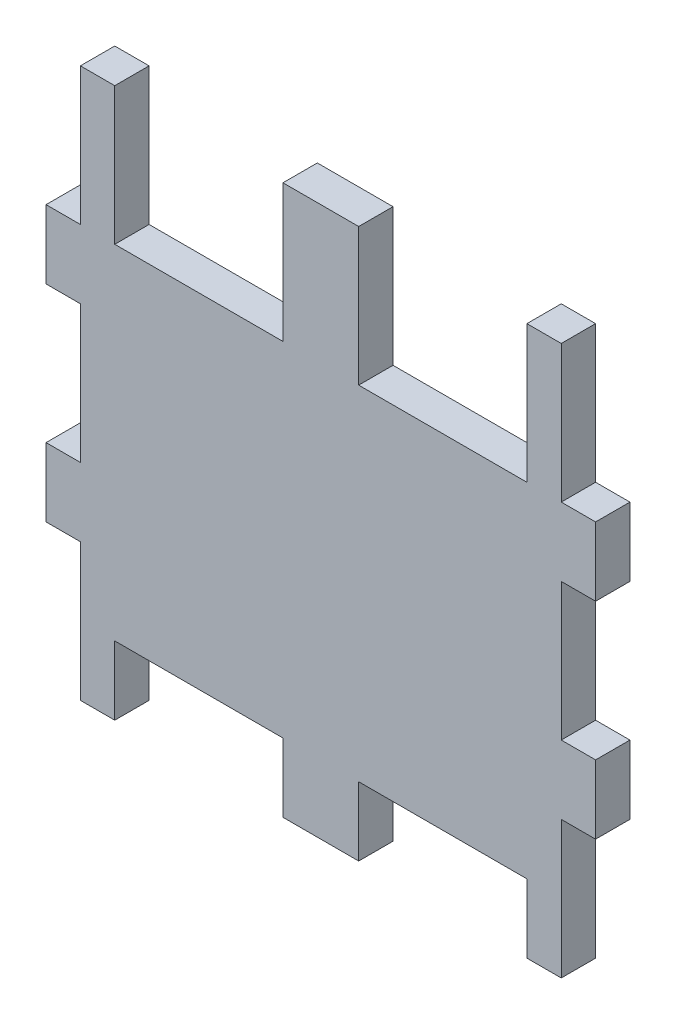
SolidWorks part; units mm, degrees
ref_plane "Front Plane" through (0, 0, 0) normal (0, 0, 1) x (1, 0, 0)
ref_plane "Top Plane" through (0, 0, 0) normal (0, 1, 0) x (1, 0, 0)
ref_plane "Right Plane" through (0, 0, 0) normal (1, 0, 0) x (0, 0, -1)
sketch "Sketch2" plane through (0, 0, 0) normal (0, 0, 1) x (1, 0, 0)
  line L1 (-50.8, -50.8) -> (50.8, -50.8)
  line L2 (-50.8, -50.8) -> (-50.8, 50.8)
  line L3 (-50.8, 50.8) -> (50.8, 50.8)
  line L4 (50.8, -50.8) -> (50.8, 50.8)
  line L5 (-50.8, -50.8) -> (50.8, 50.8) construction
  line L6 (-50.8, 50.8) -> (50.8, -50.8) construction
  point P0 (0, 0)
  dimension "D1" = 101.6
  dimension "D2" = 101.6
extrude "Boss-Extrude3" add sketch "Sketch2" along normal blind 6.35
sketch "Sketch3" plane through (0, 0, 6.35) normal (0, 0, 1) x (1, 0, 0)
  line L0 (50.8, 50.8) -> (-50.8, 50.8) construction
  line L1 (-50.8, 50.8) -> (-38.1, 50.8)
  line L2 (-50.8, 50.8) -> (-50.8, 49.8)
  line L3 (-50.8, 49.8) -> (-38.1, 49.8)
  line L4 (-38.1, 50.8) -> (-38.1, 49.8)
  line L5 (-7, 50.8) -> (7, 50.8)
  line L6 (-7, 50.8) -> (-7, 25.4)
  line L7 (-7, 25.4) -> (7, 25.4)
  line L8 (7, 50.8) -> (7, 25.4)
  line L9 (50.8, -50.8) -> (50.8, 50.8) construction
  line L10 (50.8, 50.8) -> (38.1001, 50.8)
  line L11 (50.8, 50.8) -> (50.8, 25.4)
  line L12 (50.8, 25.4) -> (38.1001, 25.4)
  line L13 (38.1001, 50.8) -> (38.1001, 25.4)
  line L14 (-7, 50.8) -> (7, 25.4) construction
  line L15 (-44.45, 50.8) -> (-44.45, 25.4)
  line L16 (-50.8, -50.8) -> (50.8, -50.8) construction
  line L17 (-38.1, 50.8) -> (-7, 50.8) construction
  line L18 (7, 25.4) -> (38.1001, 25.4) construction
  line L19 (-44.45, 12.7) -> (-44.45, 25.4)
  line L20 (-38.1, 50.8) -> (-7, 50.8)
  line L21 (-38.1, 50.8) -> (-38.1, 25.4)
  line L22 (-38.1, 25.4) -> (-7, 25.4)
  line L23 (-7, 50.8) -> (-7, 25.4)
  line L24 (7, 50.8) -> (38.1001, 50.8)
  line L25 (7, 50.8) -> (7, 25.4)
  line L26 (7, 25.4) -> (38.1001, 25.4)
  line L27 (38.1001, 50.8) -> (38.1001, 25.4)
  line L28 (-50.8, 50.8) -> (-50.8, -50.8) construction
  line L29 (-44.45, -44.45) -> (-50.8, -44.45)
  line L30 (-38.1, -50.8) -> (-6.9995, -50.8) construction
  line L31 (0, -50.8) -> (0, 50.8) construction
  line L32 (44.45, -44.45) -> (44.45, -50.8)
  line L33 (-44.45, -25.4) -> (-44.45, -25.4652)
  line L34 (6.9995, -38.1) -> (38.1, -38.1)
  line L35 (6.9995, -38.1) -> (6.9995, -50.8)
  line L36 (6.9995, -50.8) -> (38.1, -50.8)
  line L37 (-38.1, -38.1) -> (-7.0005, -38.1)
  line L38 (-38.1, -50.8) -> (-38.1, -38.1)
  line L39 (-38.1, -50.8) -> (-6.9995, -50.8)
  line L40 (38.1, -38.1) -> (38.1, -50.8)
  line L41 (-44.45, -44.45) -> (-44.45, -50.8)
  line L42 (-44.45, -50.8) -> (-44.561, -50.8221)
  line L43 (44.45, -50.8) -> (50.8, -50.8)
  line L44 (6.9995, -50.6304) -> (6.9995, -38.1)
  line L45 (-7.0005, -38.1) -> (6.9995, -38.1)
  line L46 (-6.9995, -50.8) -> (-7.0005, -38.1)
  line L47 (-6.9995, -50.8) -> (6.9995, -50.6304)
  line L48 (-38.1, -50.8) -> (-38.1, -25.4652)
  line L49 (-50.8, 0) -> (50.8, 0) construction
  line L50 (-50.8, -50.8) -> (-50.8, -38.1652)
  line L51 (-50.8, -50.8) -> (-38.1, -50.8)
  line L52 (-50.8, 0) -> (-44.45, 0) construction
  line L53 (-44.45, -12.7) -> (-44.45, -25.4)
  line L54 (44.45, -12.7) -> (44.45, 0)
  line L55 (50.8, -44.45) -> (50.8, -50.8)
  line L56 (-50.8, -50.8) -> (-44.45, -50.8)
  line L57 (-50.8, -50.8) -> (-50.8, 50.8)
  line L58 (-50.8, 50.8) -> (-44.45, 50.8)
  line L59 (44.45, 0) -> (44.45, 12.7)
  line L60 (50.8, 50.8) -> (44.45, 50.8)
  line L61 (50.8, 50.8) -> (50.8, -50.8)
  line L62 (50.8, -50.8) -> (44.45, -50.8)
  line L63 (38.1, -38.1) -> (44.45, -38.1)
  line L64 (38.1, -38.1) -> (38.1, -50.8)
  line L65 (38.1, -50.8) -> (44.45, -50.8)
  line L66 (5.4814, -37.6078) -> (5.4804, -24.9078)
  line L67 (-38.1, 25.4) -> (-44.45, 25.4)
  line L68 (-50.8, -25.4) -> (-44.45, -25.4)
  line L69 (-50.8, -25.4) -> (-50.8, -50.8)
  line L70 (-50.8, -50.8) -> (-44.45, -50.8)
  line L71 (-44.45, -44.45) -> (-44.45, -25.4)
  line L72 (-44.45, -12.7) -> (-50.8, -12.7)
  line L73 (-44.45, -12.7) -> (-44.45, 12.7)
  line L74 (-44.45, 12.7) -> (-50.8, 12.7)
  line L75 (-50.8, -12.7) -> (-50.8, 12.7)
  line L76 (-50.8, 50.8) -> (-44.45, 50.8)
  line L77 (-50.8, 50.8) -> (-50.8, 25.4)
  line L78 (-50.8, 25.4) -> (-44.45, 25.4)
  line L79 (44.45, 12.7) -> (43.5584, 12.2811)
  line L80 (-44.45, -25.4652) -> (-38.1, -25.4652)
  line L82 (-44.45, -50.8) -> (-38.1, -50.8)
  line L83 (-38.1, -25.4652) -> (-38.1, -50.8)
  line L84 (-50.8, -38.1652) -> (-50.8, -50.8)
  line L85 (-50.8, -50.8) -> (-44.45, -50.8)
  line L88 (44.45, 12.7) -> (44.45, 25.4)
  line L89 (44.45, 50.8) -> (50.8, 50.8)
  line L91 (50.8, 0) -> (44.45, 0) construction
  line L92 (44.45, 50.8) -> (44.45, 25.4)
  line L93 (50.8, 20.1539) -> (50.8, 50.8)
  line L94 (50.8, -50.8) -> (44.45, -50.8)
  line L95 (50.8, -44.45) -> (50.8, -50.8)
  line L99 (50.8, 50.8) -> (50.8, 20.1539)
  line L100 (50.8, 50.8) -> (44.45, 50.8)
  line L101 (50.8, -12.7) -> (50.8, 12.7)
  line L102 (44.45, 12.7) -> (50.8, 12.7)
  line L106 (50.8, -50.8) -> (44.45, -50.8)
  line L107 (50.8, -25.4) -> (50.8, -50.8)
  line L109 (44.45, -50.8) -> (50.8, -50.8)
  line L111 (50.8, 50.8) -> (44.45, 50.8)
  line L112 (50.8, -50.8) -> (50.8, 50.8)
  line L113 (50.8, -50.8) -> (44.45, -50.8)
  line L114 (50.8, -50.8) -> (50.8, -44.45)
  line L115 (50.8, 50.8) -> (50.8, 44.45)
  line L117 (-4.3983, -44.45) -> (0, -44.45) construction
  line L118 (0, -38.1) -> (0, -50.8) construction
  line L119 (50.8, -25.4) -> (50.8, -50.8)
  line L123 (50.8, -25.4) -> (50.8, -12.7)
  line L125 (44.45, -25.4) -> (44.45, -44.45)
  line L126 (44.45, -44.45) -> (50.8, -44.45)
  line L127 (50.8, -25.4) -> (50.8, -44.45)
  line L128 (44.45, -12.7) -> (50.8, -12.7)
  line L129 (44.45, -12.7) -> (44.45, -25.4)
  line L130 (44.45, -25.4) -> (50.8, -25.4)
  line L131 (50.8, -12.7) -> (50.8, -25.4)
  dimension "D1" = 7
  dimension "D2" = 12.7
  dimension "D3" = 12.7
  dimension "D4" = 12.7
  dimension "D5" = 14
  dimension "D6" = 14
extrude "Cut-Extrude1" cut sketch "Sketch3" against normal through all
